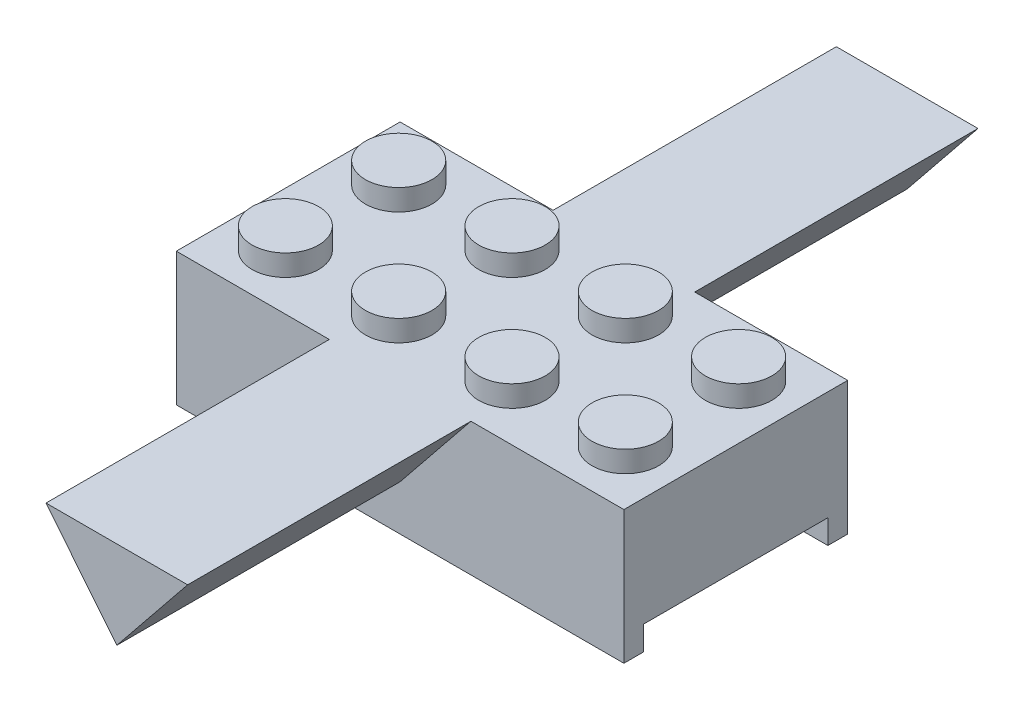
SolidWorks part; units mm, degrees
ref_plane "Front Plane" through (0, 0, 0) normal (0, 0, 1) x (1, 0, 0)
ref_plane "Top Plane" through (0, 0, 0) normal (0, 1, 0) x (1, 0, 0)
ref_plane "Right Plane" through (0, 0, 0) normal (1, 0, 0) x (0, 0, -1)
sketch "Sketch1" plane through (0, 0, 0) normal (0, 1, 0) x (1, 0, 0)
  line L1 (-17.1543, 7.4486) -> (14.4457, 7.4486)
  line L2 (-17.1543, 7.4486) -> (-17.1543, -8.3514)
  line L3 (-17.1543, -8.3514) -> (14.4457, -8.3514)
  line L4 (14.4457, 7.4486) -> (14.4457, -8.3514)
  dimension "D1" = 15.8
  dimension "D2" = 31.6
extrude "Boss-Extrude1" add sketch "Sketch1" along normal blind 9.4
sketch "Sketch2" plane through (0, 0, 0) normal (0, -1, 0) x (-1, 0, 0)
  line L0 (-14.4457, -8.3514) -> (-14.4457, 7.4486) construction
  line L1 (-14.4457, -6.9514) -> (17.1543, -6.9514)
  line L2 (-14.4457, -6.9514) -> (-14.4457, 6.0486)
  line L3 (-14.4457, 6.0486) -> (17.1543, 6.0486)
  line L4 (17.1543, -6.9514) -> (17.1543, 6.0486)
  line L5 (17.1543, 7.4486) -> (17.1543, -8.3514) construction
  line L6 (17.1543, -8.3514) -> (-14.4457, -8.3514) construction
  line L7 (-14.4457, 7.4486) -> (17.1543, 7.4486) construction
  dimension "D1" = 1.4
  dimension "D2" = 1.4
extrude "Cut-Extrude1" cut sketch "Sketch2" against normal blind 1.7
sketch "Sketch3" plane through (0, 0, -7.4486) normal (0, 0, -1) x (-1, 0, 0)
  line L0 (-14.4457, 9.4) -> (17.1543, 9.4) construction
  line L1 (-3.6457, 9.4) -> (1.3543, 3.2)
  line L2 (1.3543, 3.2) -> (6.3543, 9.4)
  line L3 (-3.6457, 9.4) -> (6.3543, 9.4)
  line L4 (17.1543, 9.4) -> (17.1543, 0) construction
  line L5 (-14.4457, 9.4) -> (-14.4457, 0) construction
  line L7 (-14.4457, 0) -> (17.1543, 0) construction
  dimension "D1" = 10
  dimension "D2" = 10.8
  dimension "D3" = 10.8
  dimension "D4" = 15.8
  dimension "D5" = 15.8
  dimension "D6" = 3.2
extrude "Boss-Extrude2" add sketch "Sketch3" along normal blind 20
sketch "Sketch4" plane through (0, 0, 8.3514) normal (0, 0, 1) x (1, 0, 0)
  line L0 (-6.3543, 9.4) -> (-1.3543, 3.2)
  line L1 (-17.1543, 9.4) -> (14.4457, 9.4) construction
  line L2 (-1.3543, 3.2) -> (3.6457, 9.4)
  line L3 (3.6457, 9.4) -> (-6.3543, 9.4)
  dimension "D1" = 0
  dimension "D2" = 0
  dimension "D3" = 0
  dimension "D4" = 0
extrude "Boss-Extrude3" add sketch "Sketch4" along normal blind 20
sketch "Sketch5" plane through (0, 9.4, 0) normal (0, 1, 0) x (1, 0, 0)
  line L0 (3.6457, -8.3514) -> (14.4457, -8.3514) construction
  line L1 (14.4457, -8.3514) -> (14.4457, 7.4486) construction
  line L2 (10.6457, -4.4514) -> (2.6457, -4.4514) construction
  circle A0 centre (10.6457, -4.4514) radius 2.35
  circle A1 centre (2.6457, -4.4514) radius 2.35
  circle A2 centre (-5.3543, -4.4514) radius 2.35
  circle A3 centre (-13.3543, -4.4514) radius 2.35
  circle A4 centre (2.6457, 3.5486) radius 2.35
  circle A5 centre (-5.3543, 3.5486) radius 2.35
  circle A6 centre (-13.3543, 3.5486) radius 2.35
  circle A7 centre (10.6457, 3.5486) radius 2.35
  dimension "D1" = 4.7
  dimension "D2" = 3.9
  dimension "D3" = 3.8
  dimension "D5" = 8
  dimension "D4" = 2
extrude "Boss-Extrude4" add sketch "Sketch5" along normal blind 1.5
